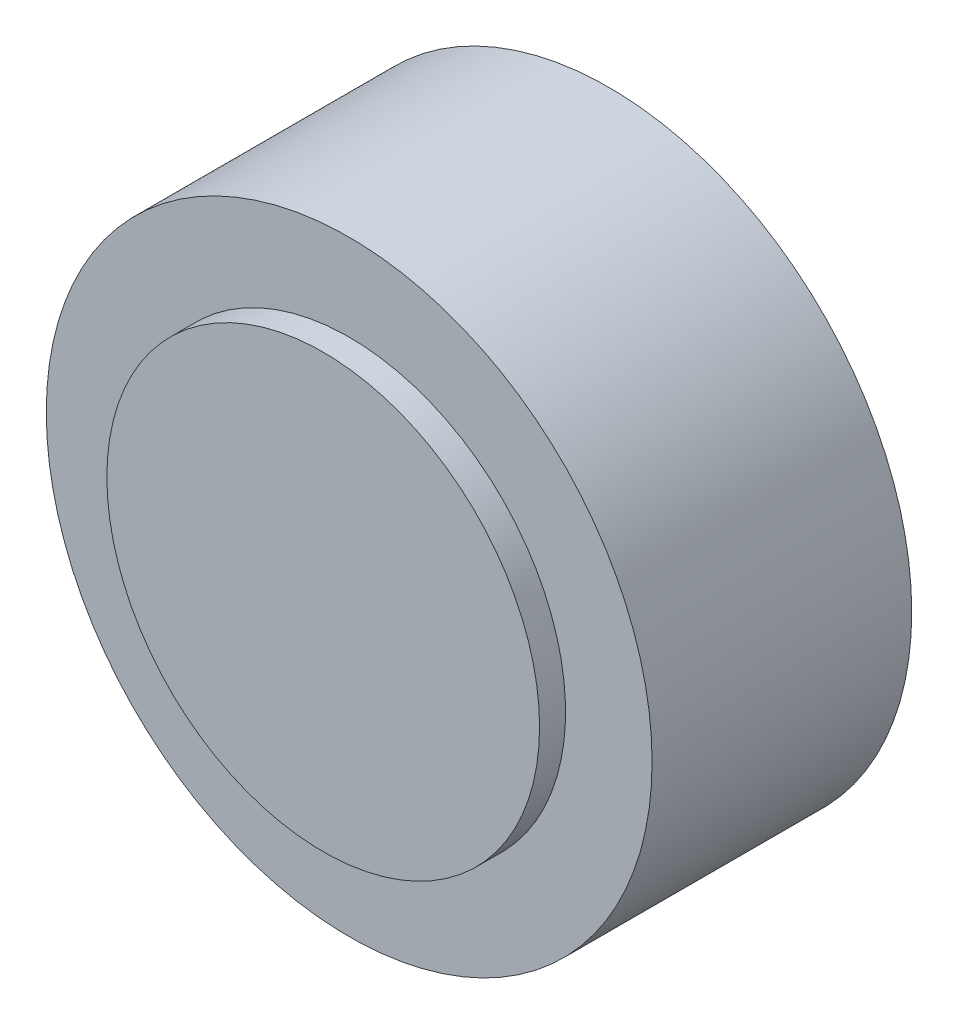
SolidWorks part; units mm, degrees
ref_plane "Plan de face" through (0, 0, 0) normal (0, 0, 1) x (1, 0, 0)
ref_plane "Plan de dessus" through (0, 0, 0) normal (0, 1, 0) x (1, 0, 0)
ref_plane "Plan de droite" through (0, 0, 0) normal (1, 0, 0) x (0, 0, -1)
sketch "Esquisse1" plane through (0, 0, 0) normal (0, 0, 1) x (1, 0, 0)
  circle A0 centre (0, 0) radius 25
  point P14 (0, 0)
  dimension "D1" = 50
extrude "Boss.-Extru.1" add sketch "Esquisse1" along normal blind 35
sketch "Esquisse3" plane through (0, 0, 0) normal (0, 0, -1) x (-1, 0, 0)
  circle A2 centre (0, 0) radius 25 construction
  circle A3 centre (0, 0) radius 35
  circle A4 centre (0, 0) radius 35
  circle A5 centre (0, 0) radius 25
  dimension "D1" = 10
extrude "Boss.-Extru.2" add sketch "Esquisse3" against normal blind 30 from offset 2 offset against normal yes
sketch "Esquisse4" plane through (0, 0, 0) normal (0, 0, -1) x (-1, 0, 0)
  circle A0 centre (0, 0) radius 2
  circle A2 centre (0, 0) radius 7
  dimension "D1" = 4
  dimension "D2" = 5
extrude "Boss.-Extru.3" add sketch "Esquisse4" along normal blind 5
sketch "Esquisse5" plane through (0, 0, 0) normal (0, 1, 0) x (1, 0, 0)
  line L0 (2, 5) -> (-2, 5) construction
  line L1 (2, 5) -> (-2, 5)
  line L2 (25, 0) -> (-25, 0) construction
  line L3 (25, 0) -> (-25, 0)
  line L4 (-7, 5) -> (-7, 0) construction
  line L5 (-7, 5) -> (-7, 0)
  circle A0 centre (0, 2.5) radius 1.5
  point P10 (-7, 2.5)
  dimension "D1" = 3
extrude "Enlèv. mat.-Extru.1" cut sketch "Esquisse5" along normal through all contours A0
